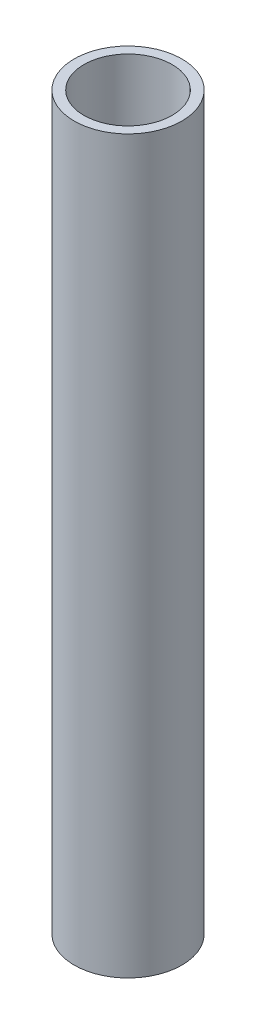
SolidWorks part; units mm, degrees
material "AISI 316 Stainless Steel Sheet (SS)"
ref_plane "Front Plane" through (0, 0, 0) normal (0, 0, 1) x (1, 0, 0)
ref_plane "Top Plane" through (0, 0, 0) normal (0, 1, 0) x (1, 0, 0)
ref_plane "Right Plane" through (0, 0, 0) normal (1, 0, 0) x (0, 0, -1)
sketch "Sketch1" plane through (0, 37.4527, 0) normal (0, -1, 0) x (1, 0, 0)
  circle A0 centre (0.7, -1.6) radius 0.7366
  circle A1 centre (0.7, -1.6) radius 0.6033
  dimension "D1" = 1.4732
  dimension "D2" = 1.2065
extrude "Boss-Extrude1" add sketch "Sketch1" along normal blind 10
